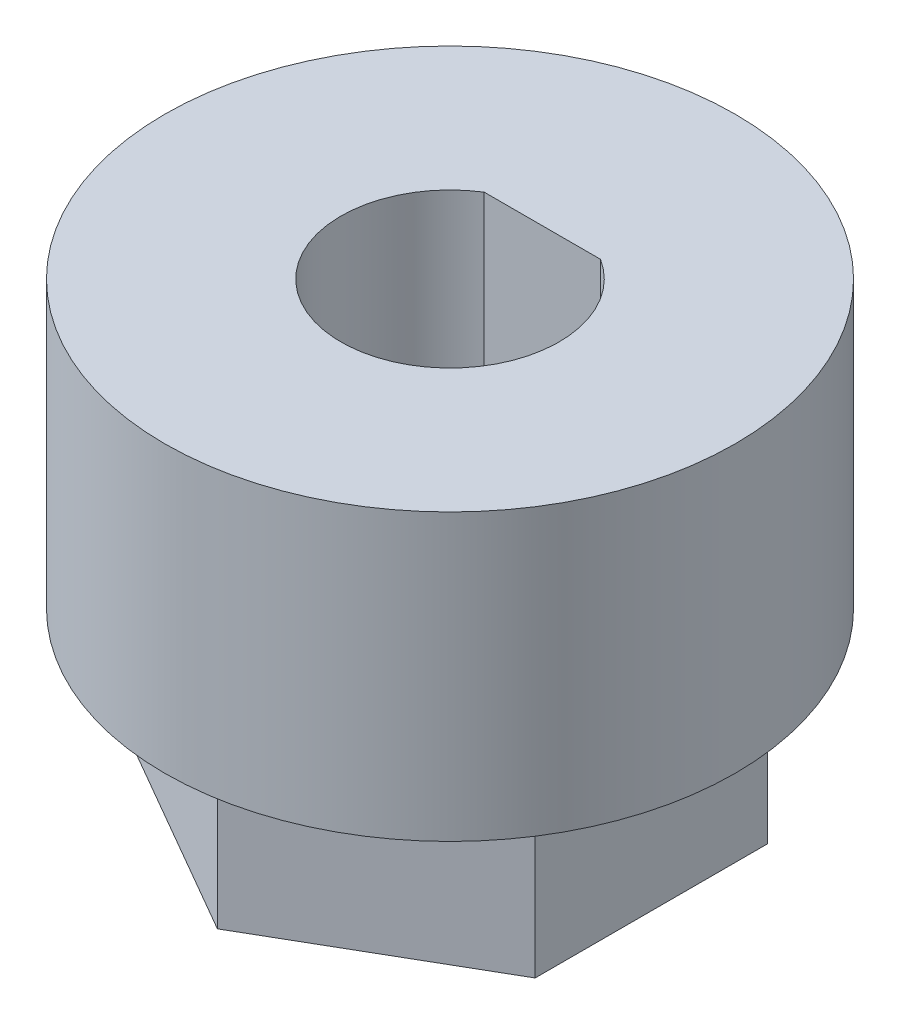
SolidWorks part; units mm, degrees
ref_plane "Front Plane" through (0, 0, 0) normal (0, 0, 1) x (1, 0, 0)
ref_plane "Top Plane" through (0, 0, 0) normal (0, 1, 0) x (1, 0, 0)
ref_plane "Right Plane" through (0, 0, 0) normal (1, 0, 0) x (0, 0, -1)
sketch "Sketch1" plane through (0, 0, 0) normal (0, 1, 0) x (1, 0, 0)
  line L0 (0, 6.9282) -> (0, -6.9282) construction
  line L1 (-6, -3.4641) -> (6, 3.4641) construction
  line L2 (6, -3.4641) -> (-6, 3.4641) construction
  line L3 (-6, 3.4641) -> (0, 6.9282)
  line L4 (0, 6.9282) -> (6, 3.4641)
  line L5 (6, 3.4641) -> (6, -3.4641)
  line L6 (6, -3.4641) -> (0, -6.9282)
  line L7 (0, -6.9282) -> (-6, -3.4641)
  line L8 (-6, -3.4641) -> (-6, 3.4641)
  dimension "D1" = 60
  dimension "D2" = 60
  dimension "D3" = 12
extrude "Boss-Extrude1" add sketch "Sketch1" along normal blind 4.8
sketch "Sketch2" plane through (0, 4.8, 0) normal (0, 1, 0) x (1, 0, 0)
  circle A0 centre (0, 0) radius 8.5
  dimension "D1" = 17
extrude "Boss-Extrude2" add sketch "Sketch2" along normal blind 8.5
sketch "Sketch3" plane through (0, 13.3, 0) normal (0, 1, 0) x (1, 0, 0)
  line L0 (-1.6583, 2.5) -> (1.6583, 2.5) construction
  line L1 (-3.5908, -3) -> (3.9178, -3) construction
  line L2 (-1.7321, 2.75) -> (1.7321, 2.75)
  arc A0 (-1.6583, 2.5) -> (1.6583, 2.5) centre (0, 0) ccw construction
  arc A1 (-1.7321, 2.75) -> (1.7321, 2.75) centre (0, 0) ccw
  dimension "D1" = 3
  dimension "D2" = 5.5
  dimension "D3" = 0.25
extrude "Cut-Extrude1" cut sketch "Sketch3" against normal through all
